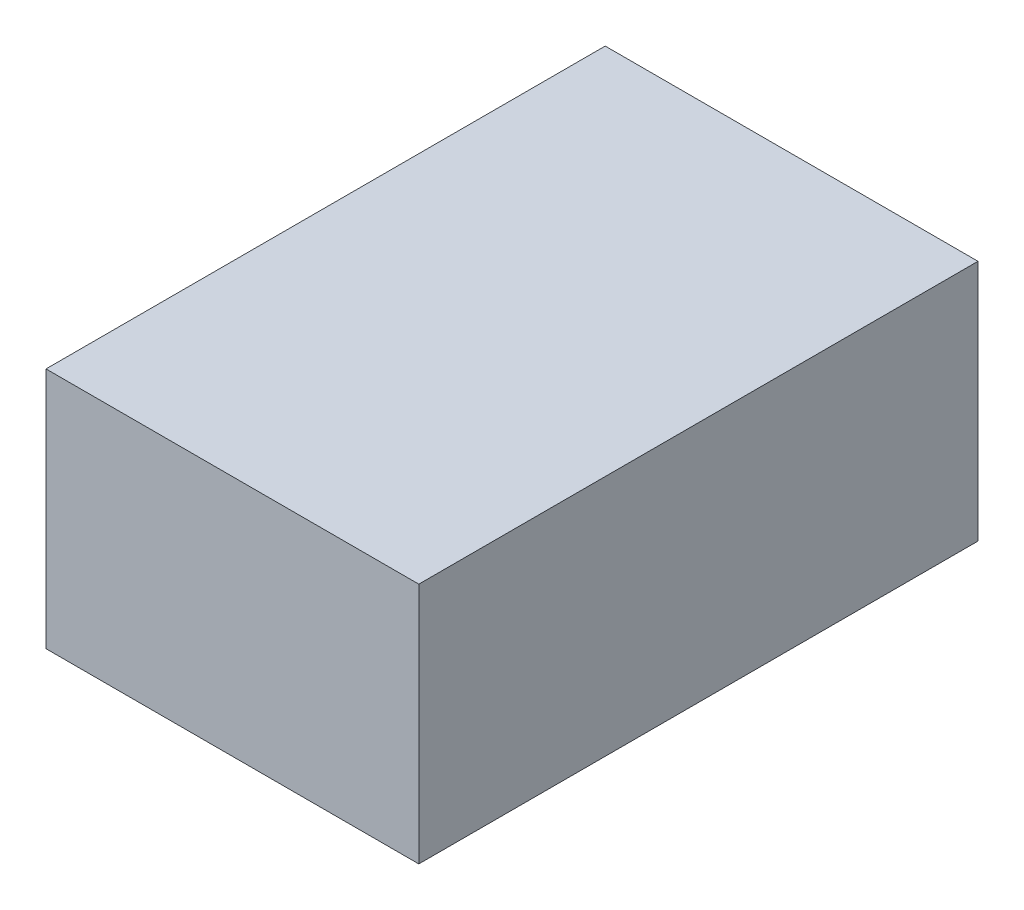
SolidWorks part; units mm, degrees
ref_plane "Front Plane" through (0, 0, 0) normal (0, 0, 1) x (1, 0, 0)
ref_plane "Top Plane" through (0, 0, 0) normal (0, 1, 0) x (1, 0, 0)
ref_plane "Right Plane" through (0, 0, 0) normal (1, 0, 0) x (0, 0, -1)
sketch "Sketch1" plane through (0, 0, 0) normal (0, 1, 0) x (1, 0, 0)
  line L1 (-5, -7.5) -> (5, -7.5)
  line L2 (-5, -7.5) -> (-5, 7.5)
  line L3 (-5, 7.5) -> (5, 7.5)
  line L4 (5, -7.5) -> (5, 7.5)
  line L5 (-5, -7.5) -> (5, 7.5) construction
  line L6 (-5, 7.5) -> (5, -7.5) construction
  point P0 (0, 0)
  dimension "D1" = 10
  dimension "D2" = 15
extrude "Boss-Extrude1" add sketch "Sketch1" along normal blind 6.5
